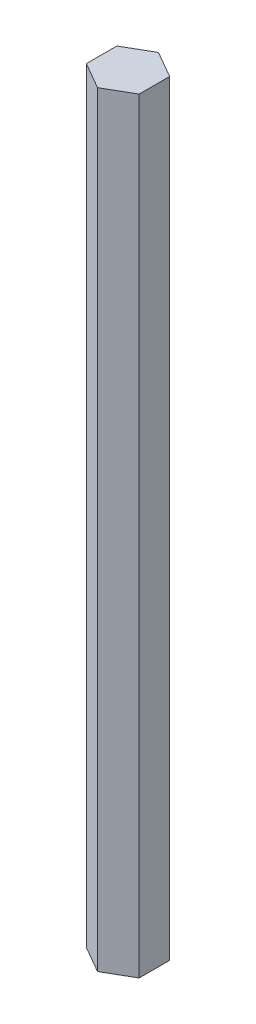
SolidWorks part; units mm, degrees
material "6061 Alloy"
ref_plane "Front Plane" through (0, 0, 0) normal (0, 0, 1) x (1, 0, 0)
ref_plane "Top Plane" through (0, 0, 0) normal (0, 1, 0) x (1, 0, 0)
ref_plane "Right Plane" through (0, 0, 0) normal (1, 0, 0) x (0, 0, -1)
sketch "Sketch1" plane through (0, 0, 0) normal (0, 1, 0) x (1, 0, 0)
  line L1 (0, 7.3323) -> (-6.35, 3.6662)
  line L2 (-6.35, 3.6662) -> (-6.35, -3.6662)
  line L3 (-6.35, -3.6662) -> (0, -7.3323)
  line L4 (0, -7.3323) -> (6.35, -3.6662)
  line L5 (6.35, -3.6662) -> (6.35, 3.6662)
  line L6 (6.35, 3.6662) -> (0, 7.3323)
  circle A0 centre (0, 0) radius 6.35 construction
  dimension "D1" = 12.7
extrude "Boss-Extrude1" add sketch "Sketch1" along normal blind 184.15
